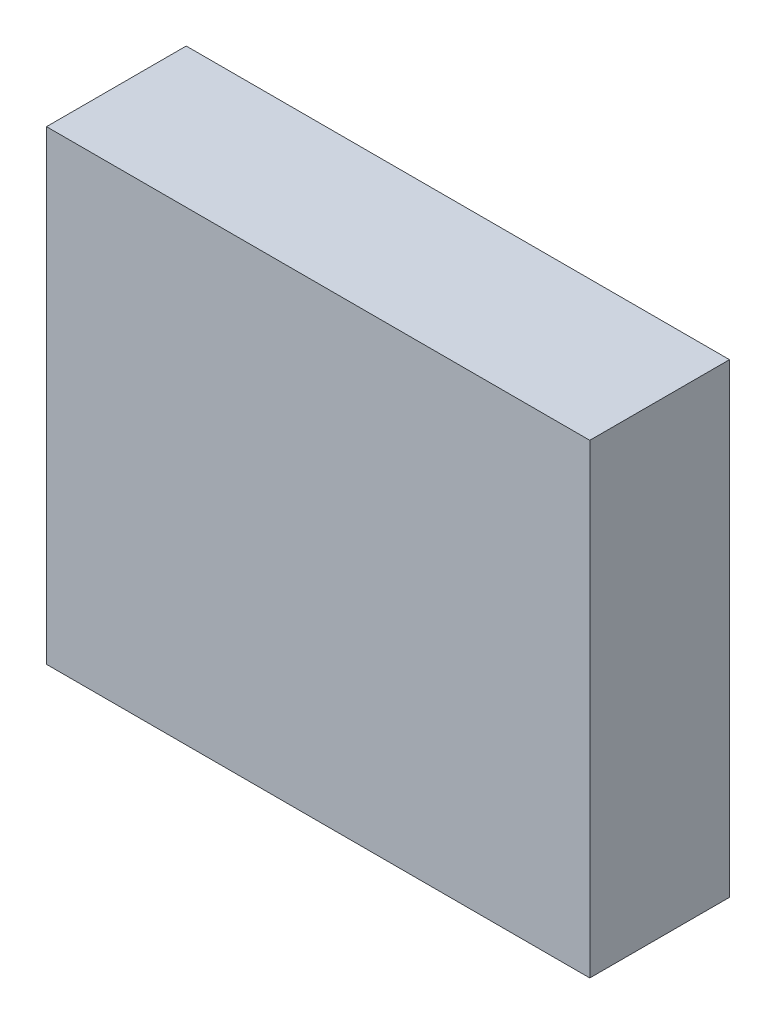
SolidWorks part; units mm, degrees
ref_plane "前视基准面" through (0, 0, 0) normal (0, 0, 1) x (1, 0, 0)
ref_plane "上视基准面" through (0, 0, 0) normal (0, 1, 0) x (1, 0, 0)
ref_plane "右视基准面" through (0, 0, 0) normal (1, 0, 0) x (0, 0, -1)
sketch "草图1" plane through (0, 0, 0) normal (0, 0, 1) x (1, 0, 0)
  line L1 (0, 0) -> (70, 0)
  line L2 (0, 0) -> (0, -60)
  line L3 (0, -60) -> (70, -60)
  line L4 (70, 0) -> (70, -60)
  dimension "D1" = 70
  dimension "D2" = 60
extrude "凸台-拉伸1" add sketch "草图1" along normal blind 18
